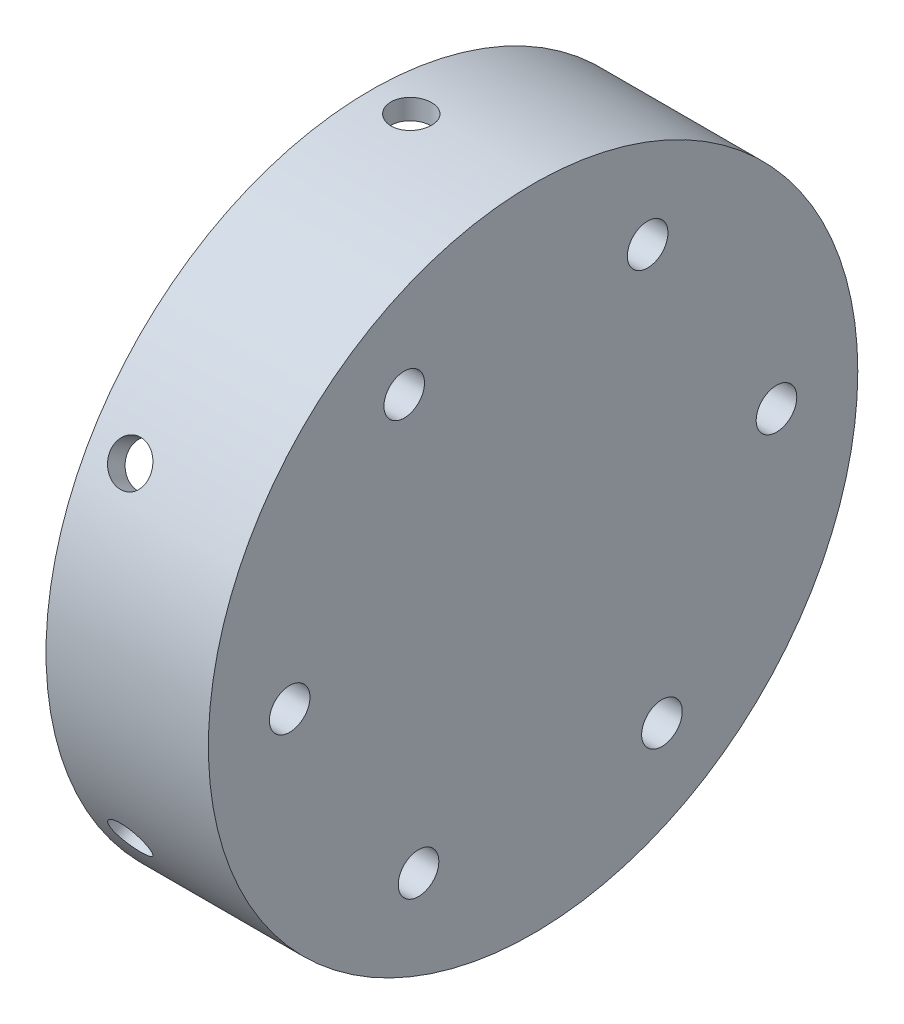
SolidWorks part; units mm, degrees
ref_plane "Front Plane" through (0, 0, 0) normal (0, 0, 1) x (1, 0, 0)
ref_plane "Top Plane" through (0, 0, 0) normal (0, 1, 0) x (1, 0, 0)
ref_plane "Right Plane" through (0, 0, 0) normal (1, 0, 0) x (0, 0, -1)
sketch "Sketch1" plane through (0, 0, 0) normal (1, 0, 0) x (0, 0, -1)
  circle A0 centre (0, 0) radius 30
  circle A1 centre (0, 0) radius 40
  dimension "D1" = 60
  dimension "D2" = 80
extrude "Boss-Extrude2" add sketch "Sketch1" along normal mid plane 20 contours A1
sketch "Sketch2" plane through (0, 0, 0) normal (1, 0, 0) x (0, 0, -1)
  circle A0 centre (14.1104, 26.4744) radius 2.5
  circle A1 centre (0, 0) radius 30 construction
  circle A2 centre (29.9827, 1.0172) radius 2.5
  circle A3 centre (15.8723, -25.4572) radius 2.5
  circle A4 centre (-14.1104, -26.4744) radius 2.5
  circle A5 centre (-29.9827, -1.0172) radius 2.5
  circle A6 centre (-15.8723, 25.4572) radius 2.5
  point P16 (0, 0)
  dimension "D1" = 5
  dimension "D3" = 30
  dimension "D2" = 6
extrude "Cut-Extrude1" cut sketch "Sketch2" against normal through all both and the other way through all
sketch "Sketch3" plane through (-10, 0, 0) normal (-1, 0, 0) x (0, 0, 1)
  circle A0 centre (0, 0) radius 37.5
  dimension "D1" = 75
extrude "Cut-Extrude2" cut sketch "Sketch3" against normal blind 10 contours A0
ref_plane "Top Bolts" through (0, 40, 0) normal (0, 1, 0) x (1, 0, 0)
sketch "Sketch4" plane through (0, 40, 0) normal (0, 1, 0) x (1, 0, 0)
  line L0 (0, 0) -> (-10, 0) construction
  line L1 (-10, 40) -> (-10, -40) construction
  circle A0 centre (-5, 0) radius 2.5
  point P5 (-5, 0)
  dimension "D1" = 5
  dimension "D2" = 5
extrude "Cut-Extrude3" cut sketch "Sketch4" against normal up to surface (2.5834 mm away)
pattern_circular "CirPattern1" count 6 over 360 about axis through (-10, 0, 0) along (1, 0, 0) of "Cut-Extrude3"
